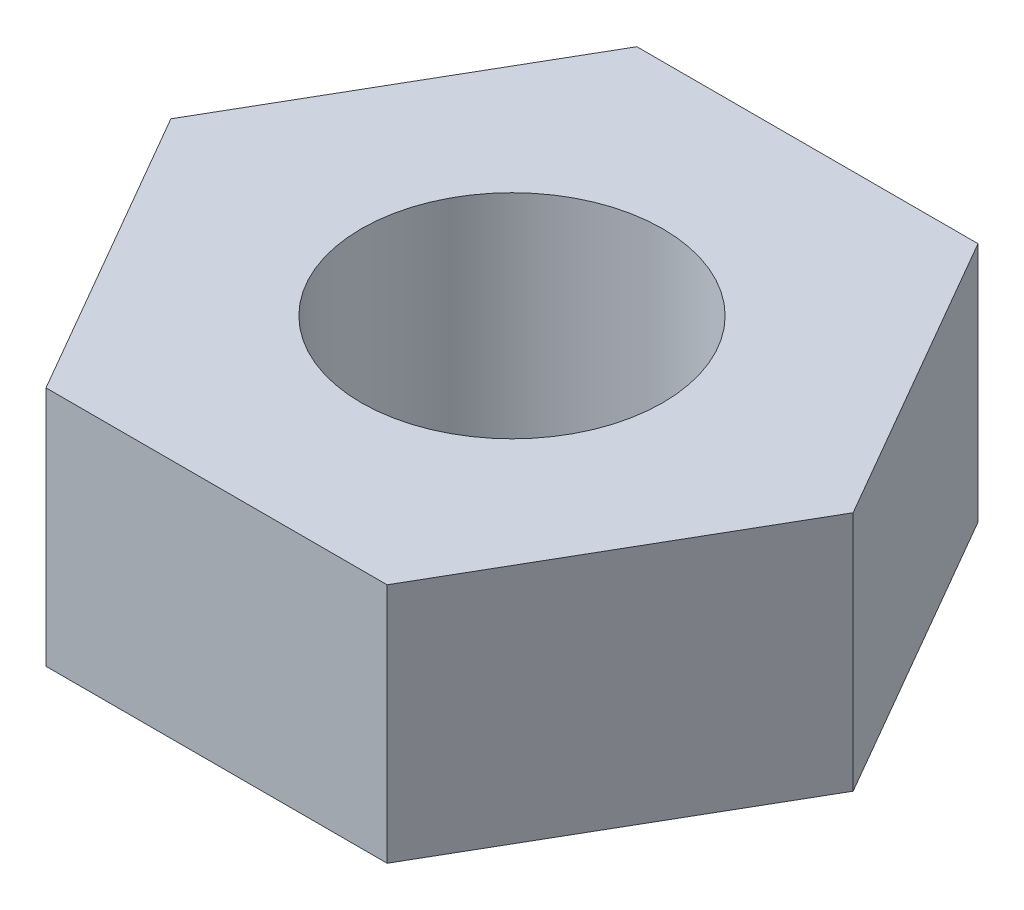
SolidWorks part; units mm, degrees
ref_plane "Front Plane" through (0, 0, 0) normal (0, 0, 1) x (1, 0, 0)
ref_plane "Top Plane" through (0, 0, 0) normal (0, 1, 0) x (1, 0, 0)
ref_plane "Right Plane" through (0, 0, 0) normal (1, 0, 0) x (0, 0, -1)
sketch "Sketch1" plane through (0, 0, 0) normal (0, 1, 0) x (1, 0, 0)
  line L1 (1.4145, 2.45) -> (-1.4145, 2.45)
  line L2 (-1.4145, 2.45) -> (-2.829, 0)
  line L3 (-2.829, 0) -> (-1.4145, -2.45)
  line L4 (-1.4145, -2.45) -> (1.4145, -2.45)
  line L5 (1.4145, -2.45) -> (2.829, 0)
  line L6 (2.829, 0) -> (1.4145, 2.45)
  circle A0 centre (0, 0) radius 2.45 construction
  circle A1 centre (0, 0) radius 1.25
  dimension "D2" = 2.5
  dimension "D1" = 4.9
extrude "Boss-Extrude1" add sketch "Sketch1" along normal blind 2
